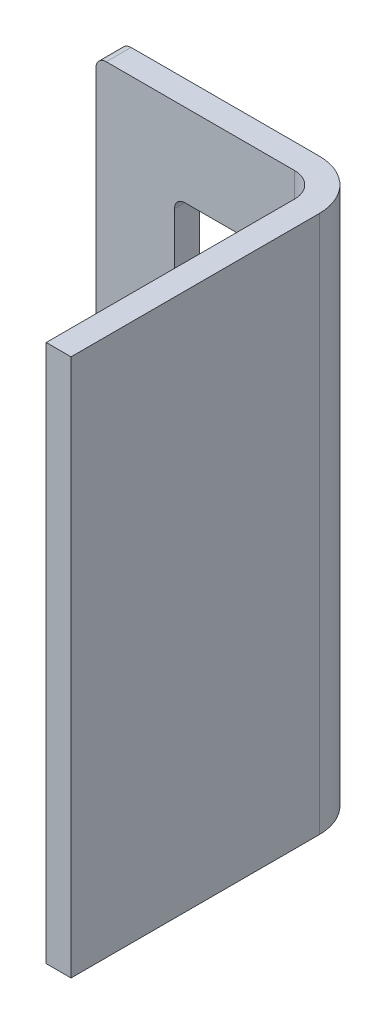
SolidWorks part; units mm, degrees
ref_plane "前视基准面" through (0, 0, 0) normal (0, 0, 1) x (1, 0, 0)
ref_plane "上视基准面" through (0, 0, 0) normal (0, 1, 0) x (1, 0, 0)
ref_plane "右视基准面" through (0, 0, 0) normal (1, 0, 0) x (0, 0, -1)
other "Configuration Table"
ref_plane "基准面_卡耳截面Y125点5" through (0, 125.5, 0) normal (0, 1, 0) x (1, 0, 0)
sketch "草图_L形卡耳_内伸12_厚1点2_内R1点2_焊脚12" plane through (0, 125.5, 0) normal (0, 1, 0) x (1, 0, 0)
  line L0 (59.2, 303.8) -> (68.8, 303.8)
  line L1 (71.2, 301.4) -> (71.2, 289.4)
  line L2 (71.2, 289.4) -> (70, 289.4)
  line L3 (70, 289.4) -> (70, 301.4)
  line L4 (68.8, 302.6) -> (59.2, 302.6)
  line L5 (59.2, 302.6) -> (59.2, 303.8)
  arc A0 (68.8, 303.8) -> (71.2, 301.4) centre (68.8, 301.4) cw
  arc A1 (70, 301.4) -> (68.8, 302.6) centre (68.8, 301.4) ccw
extrude "拉伸_卡耳外高26" add sketch "草图_L形卡耳_内伸12_厚1点2_内R1点2_焊脚12" along normal blind 26
ref_plane "基准面_卡耳接舌槽" through (0, 0, -302.6) normal (0, 0, 1) x (1, 0, 0)
sketch "草图_卡槽矩形_净高18_净宽5_中心Y138点5" plane through (0, 0, -302.6) normal (0, 0, 1) x (1, 0, 0)
  line L1 (63, 129.5) -> (68, 129.5)
  line L2 (63, 129.5) -> (63, 147.5)
  line L3 (63, 147.5) -> (68, 147.5)
  line L4 (68, 129.5) -> (68, 147.5)
  line L5 (63, 129.5) -> (68, 147.5) construction
  line L6 (63, 147.5) -> (68, 129.5) construction
  point P0 (65.5, 138.5)
  dimension "卡槽净宽5" = 5
  dimension "卡槽净高18" = 18
extrude "切除_卡槽18乘5" cut sketch "草图_卡槽矩形_净高18_净宽5_中心Y138点5" against normal blind 1.2
fillet "圆角_R0点5_卡槽四内角" radius 0.5 4 edges at (68, 147.5, -303.2) (63, 147.5, -303.2) (63, 129.5, -303.2) (68, 129.5, -303.2)
fillet "圆角_R0点5_卡耳自由端两角" radius 0.5 2 edges at (59.2, 125.5, -303.2) (59.2, 151.5, -303.2)
